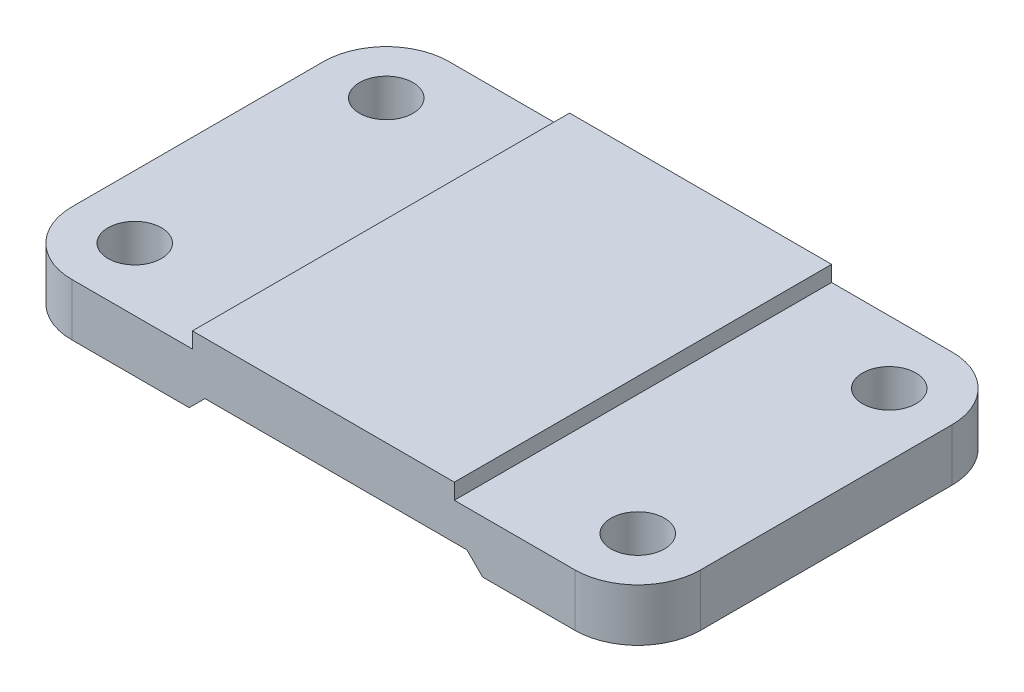
SolidWorks part; units mm, degrees
ref_plane "Front Plane" through (0, 0, 0) normal (0, 0, 1) x (1, 0, 0)
ref_plane "Top Plane" through (0, 0, 0) normal (0, 1, 0) x (1, 0, 0)
ref_plane "Right Plane" through (0, 0, 0) normal (1, 0, 0) x (0, 0, -1)
sketch "Sketch1" plane through (0, 0, 0) normal (0, 1, 0) x (1, 0, 0)
  line L0 (0, 36) -> (0, -36) construction
  line L1 (48, 36) -> (-48, 36)
  line L2 (60, 24) -> (60, -24)
  line L3 (48, -36) -> (-48, -36)
  line L4 (-60, 24) -> (-60, -24)
  line L5 (60, 36) -> (-60, -36) construction
  line L6 (60, -36) -> (-60, 36) construction
  line L7 (-60, 0) -> (60, 0) construction
  arc A0 (-48, -36) -> (-60, -24) centre (-48, -24) cw
  arc A1 (60, -24) -> (48, -36) centre (48, -24) cw
  arc A2 (48, 36) -> (60, 24) centre (48, 24) cw
  arc A3 (-48, 36) -> (-60, 24) centre (-48, 24) ccw
  circle A4 centre (-48, 24) radius 5.1
  circle A5 centre (-48, -24) radius 5.1
  circle A6 centre (48, -24) radius 5.1
  circle A7 centre (48, 24) radius 5.1
  point P0 (0, 0)
  dimension "D3" = 12
  dimension "D4" = 10.2
  dimension "D1" = 72
  dimension "D2" = 120
extrude "Boss-Extrude1" add sketch "Sketch1" along normal blind 10
cosmetic thread "Cosmetic Thread1" parameters "D1"=6, "D2"=12
cosmetic thread "Cosmetic Thread2" parameters "D1"=6, "D2"=12
cosmetic thread "Cosmetic Thread3" parameters "D1"=6, "D2"=12
cosmetic thread "Cosmetic Thread4" parameters "D1"=6, "D2"=12
sketch "Sketch2" plane through (0, 10, 0) normal (0, 1, 0) x (1, 0, 0)
  line L0 (48, 36) -> (-48, 36) construction
  line L1 (25, -36) -> (-25, -36)
  line L2 (25, -36) -> (25, 36)
  line L3 (25, 36) -> (-25, 36)
  line L4 (-25, -36) -> (-25, 36)
  line L5 (25, -36) -> (-25, 36) construction
  line L6 (25, 36) -> (-25, -36) construction
  point P0 (0, 0)
  dimension "D1" = 50
extrude "Boss-Extrude2" add sketch "Sketch2" along normal blind 3
sketch "Sketch3" plane through (0, 0, 36) normal (0, 0, 1) x (1, 0, 0)
  line L0 (0, 0) -> (-25.6043, 0)
  line L1 (-48, 0) -> (48, 0) construction
  line L2 (-25.6043, 0) -> (-22.6043, 3)
  line L3 (-22.6043, 3) -> (27.3957, 3)
  line L4 (27.3957, 3) -> (30.3957, 0)
  line L5 (30.3957, 0) -> (0, 0)
  dimension "D1" = 56
  dimension "D2" = 3
  dimension "D3" = 45
extrude "Cut-Extrude1" cut sketch "Sketch3" against normal through all
